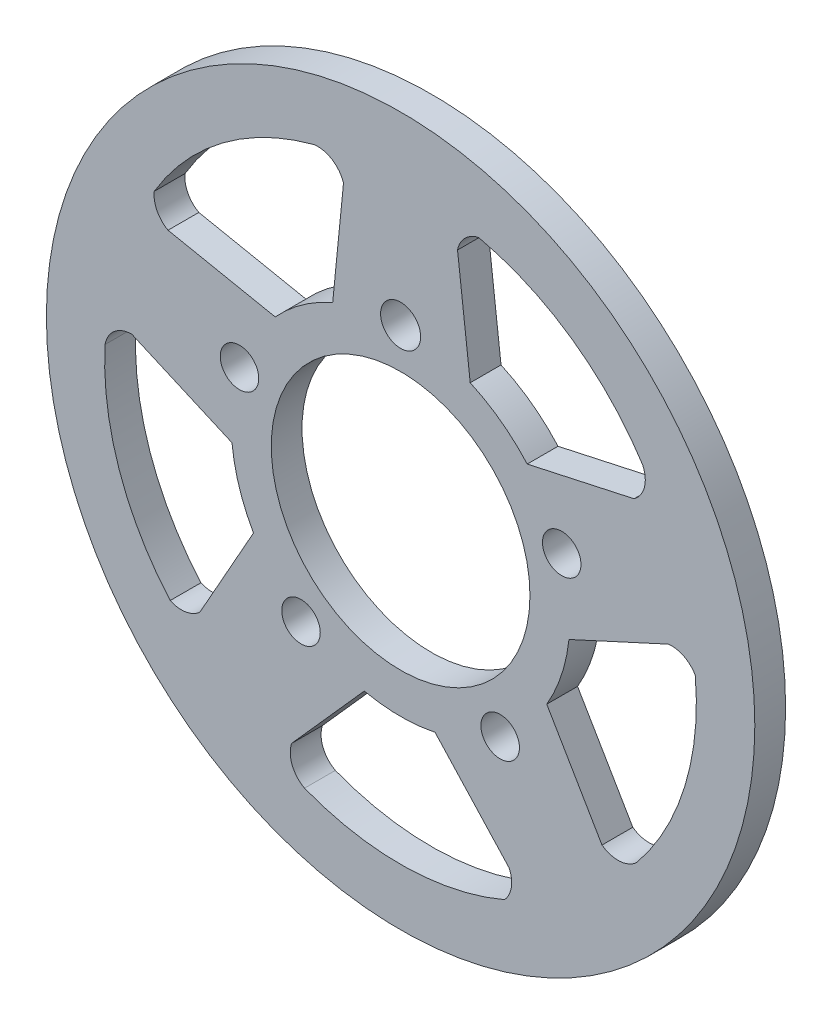
SolidWorks part; units mm, degrees
ref_plane "Front Plane" through (0, 0, 0) normal (0, 0, 1) x (1, 0, 0)
ref_plane "Top Plane" through (0, 0, 0) normal (0, 1, 0) x (1, 0, 0)
ref_plane "Right Plane" through (0, 0, 0) normal (1, 0, 0) x (0, 0, -1)
sketch "Sketch1" plane through (0, 0, 0) normal (0, 0, 1) x (1, 0, 0)
  line L0 (-132.7917, 115.8382) -> (133.875, 115.8382) construction
  line L1 (-22.0446, 50.3888) -> (-18.5394, 85.718)
  line L2 (-40.7019, 36.9912) -> (-75.5118, 43.9708)
  line L3 (22.6032, 50.1408) -> (18.4843, 85.4037)
  line L4 (41.1105, 36.5367) -> (75.7937, 44.1204)
  line L5 (54.6715, -6.0025) -> (86.9357, 8.8116)
  line L6 (47.4523, -27.8079) -> (65.3825, -58.4502)
  line L7 (11.1857, -53.8505) -> (35.2449, -79.9578)
  line L8 (-11.7834, -53.7229) -> (-35.3851, -80.2445)
  line L9 (-47.7584, -27.2789) -> (-65.1532, -58.2282)
  line L10 (-54.7348, -5.3947) -> (-87.2517, 8.8563)
  line L11 (-133.5308, 18.1497) -> (133.1359, 18.1497) construction
  circle A0 centre (0, 0) radius 55
  circle A1 centre (0, 0) radius 100
  circle A2 centre (0, 0) radius 115
  circle A3 centre (0, 55) radius 6.25
  circle A4 centre (52.3081, 16.9959) radius 6.25
  circle A5 centre (32.3282, -44.4959) radius 6.25
  circle A6 centre (-32.3282, -44.4959) radius 6.25
  circle A7 centre (-52.3081, 16.9959) radius 6.25
  arc A8 (-79.9893, 52.6676) -> (-28.1098, 91.7508) centre (-6.1767, 8.662) cw
  arc A9 (-18.5394, 85.718) -> (-28.1098, 91.7508) centre (-26.9297, 83.0152) ccw
  arc A10 (-79.9893, 52.6676) -> (-75.5118, 43.9708) centre (-71.2304, 51.6761) ccw
  arc A11 (-40.7019, 36.9912) -> (-22.0446, 50.3888) centre (0, 0) cw
  arc A12 (25.3718, 92.3495) -> (78.5738, 55.0865) centre (6.3294, 8.5511) cw
  arc A13 (75.7937, 44.1204) -> (78.5738, 55.0865) centre (70.6304, 51.2648) ccw
  arc A14 (25.3718, 92.3495) -> (18.4843, 85.4037) centre (27.1355, 83.7129) ccw
  arc A15 (95.67, 4.4075) -> (76.671, -57.7054) centre (10.0884, -3.3772) cw
  arc A16 (65.3825, -58.4502) -> (76.671, -57.7054) centre (70.5817, -51.3319) ccw
  arc A17 (95.67, 4.4075) -> (86.9357, 8.8116) centre (88.0011, 0.0613) ccw
  arc A18 (33.7555, -89.6255) -> (-31.1885, -90.7504) centre (-0.0944, -10.6383) cw
  arc A19 (-35.3851, -80.2445) -> (-31.1885, -90.7504) centre (-27.0085, -82.9896) ccw
  arc A20 (33.7555, -89.6255) -> (35.2449, -79.9578) centre (27.2521, -83.675) ccw
  arc A21 (-74.8079, -59.7992) -> (-95.9466, 1.6186) centre (-10.1468, -3.1976) cw
  arc A22 (-87.2517, 8.8563) -> (-95.9466, 1.6186) centre (-87.2739, 0.0414) ccw
  arc A23 (-74.8079, -59.7992) -> (-65.1532, -58.2282) centre (-71.1583, -51.7753) ccw
  circle A24 centre (0, 0) radius 43.5
  point P19 (0, 0)
  point P67 (0, 0)
  dimension "D1" = 110
  dimension "D2" = 200
  dimension "D3" = 230
  dimension "D4" = 12.5
  dimension "D7" = 87
  dimension "D5" = 5
  dimension "D6" = 5
extrude "Boss-Extrude1" add sketch "Sketch1" along normal blind 10 contours A2
sketch "Sketch3" plane through (0, 0, 0) normal (0, 0, 1) x (1, 0, 0)
  line L0 (-22.0446, 50.3888) -> (-18.5394, 85.718)
  line L1 (-40.7019, 36.9912) -> (-75.5118, 43.9708)
  line L2 (22.6032, 50.1408) -> (18.4843, 85.4037)
  line L3 (41.1105, 36.5367) -> (75.7937, 44.1204)
  line L4 (54.6715, -6.0025) -> (86.9357, 8.8116)
  line L5 (47.4523, -27.8079) -> (65.3825, -58.4502)
  line L6 (11.1857, -53.8505) -> (35.2449, -79.9578)
  line L7 (-11.7834, -53.7229) -> (-35.3851, -80.2445)
  line L8 (-47.7584, -27.2789) -> (-65.1532, -58.2282)
  line L9 (-54.7348, -5.3947) -> (-87.2517, 8.8563)
  circle A0 centre (0, 0) radius 55
  circle A1 centre (0, 0) radius 100
  circle A3 centre (0, 55) radius 6.5
  circle A4 centre (52.3081, 16.9959) radius 6.25
  circle A5 centre (32.3282, -44.4959) radius 6.25
  circle A6 centre (-32.3282, -44.4959) radius 6.25
  circle A7 centre (-52.3081, 16.9959) radius 6.25
  arc A8 (-79.9893, 52.6676) -> (-28.1098, 91.7508) centre (-6.1767, 8.662) cw
  arc A9 (-18.5394, 85.718) -> (-28.1098, 91.7508) centre (-26.9297, 83.0152) ccw
  arc A10 (-79.9893, 52.6676) -> (-75.5118, 43.9708) centre (-71.2304, 51.6761) ccw
  arc A11 (-40.7019, 36.9912) -> (-22.0446, 50.3888) centre (0, 0) cw
  arc A12 (25.3718, 92.3495) -> (78.5738, 55.0865) centre (6.3294, 8.5511) cw
  arc A13 (75.7937, 44.1204) -> (78.5738, 55.0865) centre (70.6304, 51.2648) ccw
  arc A14 (25.3718, 92.3495) -> (18.4843, 85.4037) centre (27.1355, 83.7129) ccw
  arc A15 (95.67, 4.4075) -> (76.671, -57.7054) centre (10.0884, -3.3772) cw
  arc A16 (65.3825, -58.4502) -> (76.671, -57.7054) centre (70.5817, -51.3319) ccw
  arc A17 (95.67, 4.4075) -> (86.9357, 8.8116) centre (88.0011, 0.0613) ccw
  arc A18 (33.7555, -89.6255) -> (-31.1885, -90.7504) centre (-0.0944, -10.6383) cw
  arc A19 (-35.3851, -80.2445) -> (-31.1885, -90.7504) centre (-27.0085, -82.9896) ccw
  arc A20 (33.7555, -89.6255) -> (35.2449, -79.9578) centre (27.2521, -83.675) ccw
  arc A21 (-74.8079, -59.7992) -> (-95.9466, 1.6186) centre (-10.1468, -3.1976) cw
  arc A22 (-87.2517, 8.8563) -> (-95.9466, 1.6186) centre (-87.2739, 0.0414) ccw
  arc A23 (-74.8079, -59.7992) -> (-65.1532, -58.2282) centre (-71.1583, -51.7753) ccw
  circle A24 centre (0, 0) radius 42
  point P16 (0, 0)
  point P61 (0, 0)
  dimension "D1" = 110
  dimension "D2" = 200
  dimension "D3" = 84
  dimension "D4" = 13
extrude "Cut-Extrude2" cut sketch "Sketch3" along normal through all contours A12 A14 L2 A0 L3 A13 | A8 A10 L1 A0 L0 A9 | A21 A23 L8 A0 L9 A22 | A18 A20 L6 A0 L7 A19 | A15 A17 L4 A0 L5 A16 | A4 | A3 | A7 | A6 | A5 | A24
ref_plane "MidPlane" through (0, 0, 5) normal (0, 0, -1) x (-1, 0, 0)
sketch "Sketch4" plane through (0, 0, 5) normal (0, 0, -1) x (-1, 0, 0)
  circle A0 centre (0, 0) radius 115
